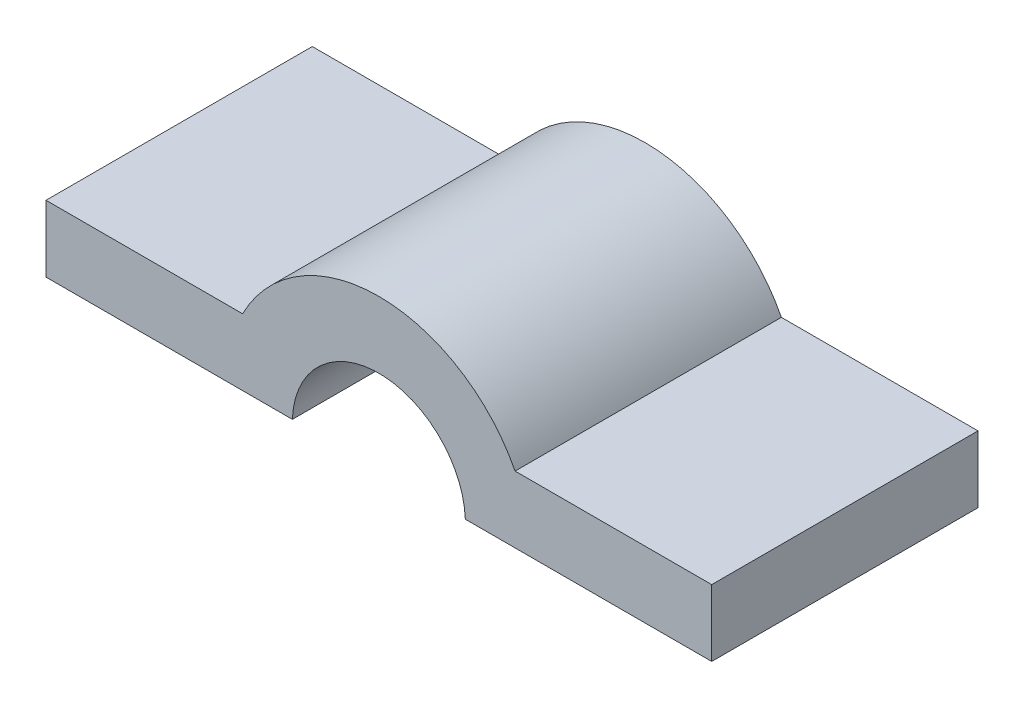
SolidWorks part; units mm, degrees
ref_plane "Front Plane" through (0, 0, 0) normal (0, 0, 1) x (1, 0, 0)
ref_plane "Top Plane" through (0, 0, 0) normal (0, 1, 0) x (1, 0, 0)
ref_plane "Right Plane" through (0, 0, 0) normal (1, 0, 0) x (0, 0, -1)
sketch "Sketch1" plane through (0, 0, 0) normal (0, 0, 1) x (1, 0, 0)
  line L0 (-25.3566, 0) -> (25.3566, 0) construction
  line L1 (-25, 0.25) -> (-11.4973, 0.25)
  line L2 (11.4973, 0.25) -> (25, 0.25)
  line L3 (25, 0.25) -> (25, 5.25)
  line L4 (25, 5.25) -> (10.2317, 5.25)
  line L5 (-25, 0.25) -> (-25, 5.25)
  line L6 (-25, 5.25) -> (-10.2317, 5.25)
  line L7 (-11.4973, 0.25) -> (-6.4952, 0.25)
  line L8 (11.4973, 0.25) -> (6.4952, 0.25)
  arc A0 (6.4952, 0.25) -> (-6.4952, 0.25) centre (0, 0) ccw
  arc A1 (10.2317, 5.25) -> (-10.2317, 5.25) centre (0, 0) ccw
  dimension "D1" = 13
  dimension "D2" = 5
  dimension "D3" = 5
  dimension "D4" = 0.25
  dimension "D5" = 50
extrude "Boss-Extrude1" add sketch "Sketch1" against normal blind 20
